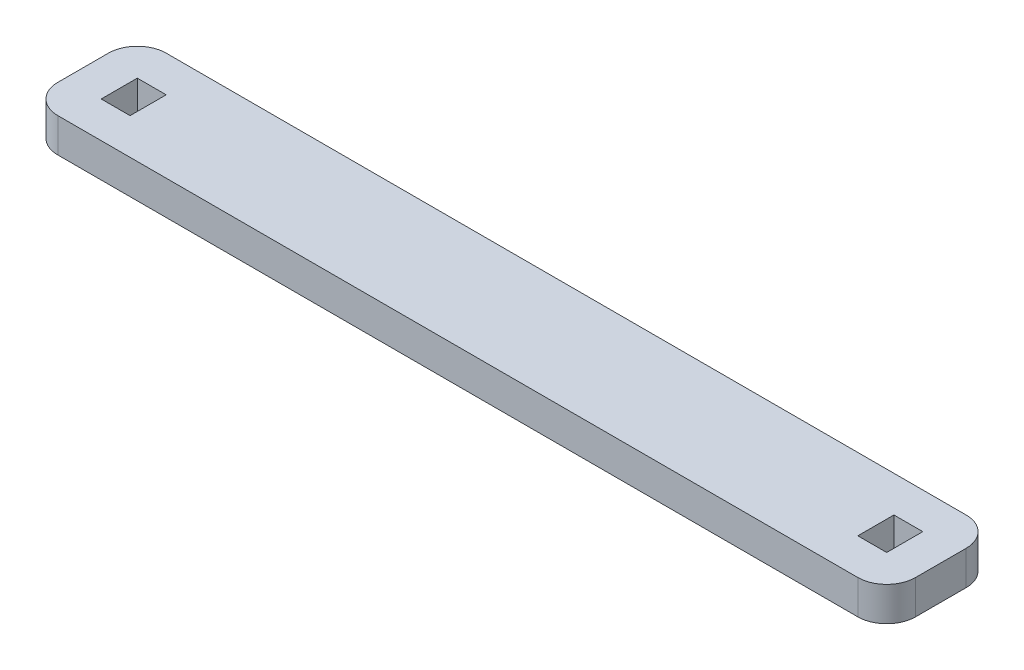
SolidWorks part; units mm, degrees
ref_plane "Front Plane" through (0, 0, 0) normal (0, 0, 1) x (1, 0, 0)
ref_plane "Top Plane" through (0, 0, 0) normal (0, 1, 0) x (1, 0, 0)
ref_plane "Right Plane" through (0, 0, 0) normal (1, 0, 0) x (0, 0, -1)
sketch "Sketch1" plane through (0, 0, 0) normal (0, 1, 0) x (1, 0, 0)
  line L0 (-33.274, 0) -> (33.274, 0) construction
  line L6 (37.719, -4.7625) -> (-37.719, -4.7625)
  line L7 (-32.004, -1.5875) -> (-34.544, -1.5875)
  line L8 (-32.004, -1.5875) -> (-32.004, 1.5875)
  line L9 (-32.004, 1.5875) -> (-34.544, 1.5875)
  line L10 (-34.544, -1.5875) -> (-34.544, 1.5875)
  line L11 (-32.004, -1.5875) -> (-34.544, 1.5875) construction
  line L12 (-32.004, 1.5875) -> (-34.544, -1.5875) construction
  line L13 (34.544, -1.5875) -> (32.004, -1.5875)
  line L14 (34.544, -1.5875) -> (34.544, 1.5875)
  line L15 (34.544, 1.5875) -> (32.004, 1.5875)
  line L16 (32.004, -1.5875) -> (32.004, 1.5875)
  line L17 (34.544, -1.5875) -> (32.004, 1.5875) construction
  line L18 (34.544, 1.5875) -> (32.004, -1.5875) construction
  line L19 (37.719, -4.7625) -> (37.719, 4.7625)
  line L20 (37.719, 4.7625) -> (-37.719, 4.7625)
  line L21 (-37.719, -4.7625) -> (-37.719, 4.7625)
  line L22 (37.719, -4.7625) -> (-37.719, 4.7625) construction
  line L23 (37.719, 4.7625) -> (-37.719, -4.7625) construction
  point P0 (0, 0)
  point P1 (0, 0)
  point P6 (-33.274, 0)
  point P11 (33.274, 0)
  dimension "D1" = 9.525
  dimension "D2" = 3.175
  dimension "D3" = 2.54
  dimension "D4" = 66.548
  dimension "D5" = 3.175
extrude "Boss-Extrude1" add sketch "Sketch1" along normal mid plane 3
fillet "Fillet1" radius 2.54 4 edges at (-37.719, 0, -4.7625) (37.719, 0, -4.7625) (37.719, 0, 4.7625) (-37.719, 0, 4.7625)
